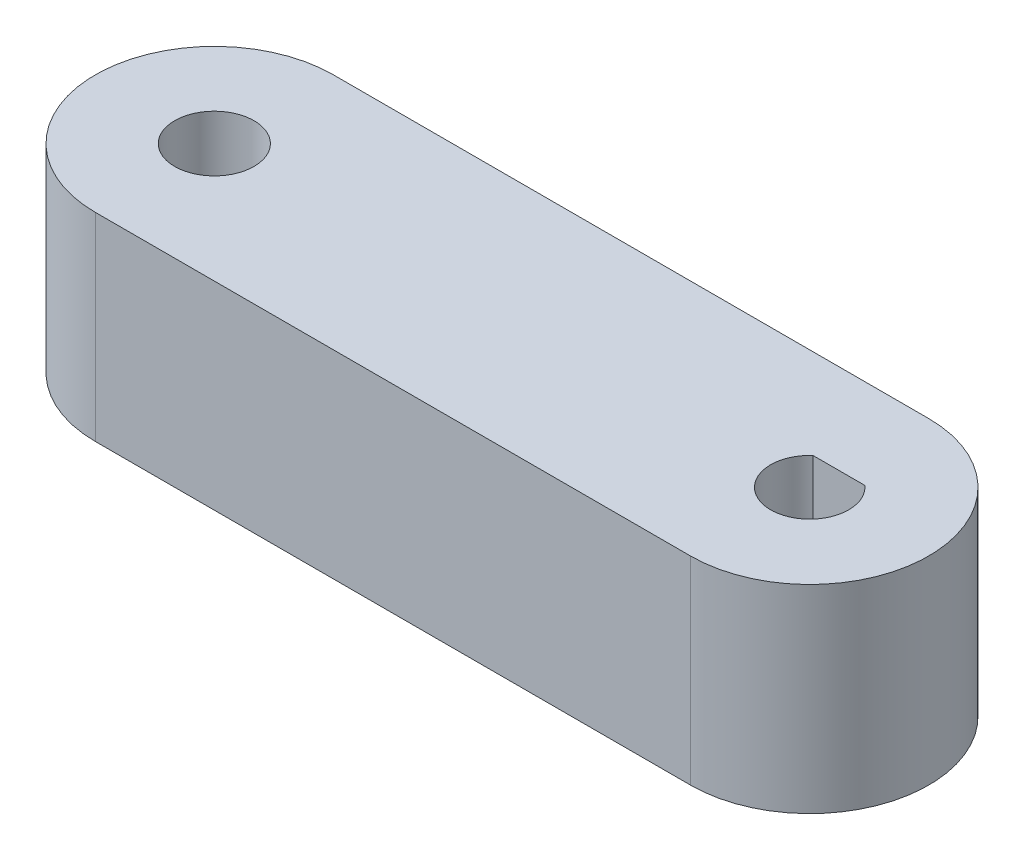
SolidWorks part; units mm, degrees
ref_plane "Front Plane" through (0, 0, 0) normal (0, 0, 1) x (1, 0, 0)
ref_plane "Top Plane" through (0, 0, 0) normal (0, 1, 0) x (1, 0, 0)
ref_plane "Right Plane" through (0, 0, 0) normal (1, 0, 0) x (0, 0, -1)
sketch "Sketch3" plane through (0, 0, 0) normal (0, 1, 0) x (1, 0, 0)
  line L0 (-31.75, 0) -> (6.35, 0) construction
  line L1 (-6.985, 0) -> (6.985, 0) construction
  line L2 (-31.75, 7.62) -> (6.35, 7.62)
  line L3 (-31.75, -7.62) -> (6.35, -7.62)
  arc A0 (-31.75, 7.62) -> (-31.75, -7.62) centre (-31.75, 0) ccw
  arc A1 (6.35, -7.62) -> (6.35, 7.62) centre (6.35, 0) ccw
  point P5 (-12.7, 0)
  dimension "D2" = 7.62
  dimension "D1" = 38.1
  dimension "D3" = 31.75
extrude "Boss-Extrude1" add sketch "Sketch3" along normal blind 12.7
sketch "Sketch4" plane through (0, 12.7, 0) normal (0, 1, 0) x (1, 0, 0)
  circle A0 centre (-31.75, 0) radius 2.54
  dimension "D1" = 5.08
extrude "Cut-Extrude3" cut sketch "Sketch4" against normal through all
sketch "Sketch6" plane through (0, 12.7, 0) normal (0, 1, 0) x (1, 0, 0)
  line L0 (4.6912, 1.8704) -> (8.0088, 1.8704)
  circle A0 centre (6.35, 0) radius 2.5
  arc A1 (8.0088, 1.8704) -> (4.6912, 1.8704) centre (6.35, 0) ccw
  dimension "D1" = 5
  dimension "D2" = 1.8704
extrude "Cut-Extrude4" cut sketch "Sketch6" against normal through all contours L0 A0
equation "\"TibiaLength\"= 5in"
equation "\"TibiaRadius\"= 0.3in"
equation "\"TibiaDistFromCentre\"= \"TibiaLength\" / 2"
equation "\"TibiaThickness\"= 0.5in"
equation "\"HoleRadius\"= 0.2in"
equation "\"D1@Sketch3\"= \"TibiaLength\" * 0.3"
equation "\"D2@Sketch3\"= \"TibiaRadius\""
equation "\"D3@Sketch3\"=\"TibiaDistFromCentre\"/2"
equation "\"D1@Boss-Extrude1\"= \"TibiaThickness\""
equation "\"D1@Sketch4\"= \"HoleRadius\""
